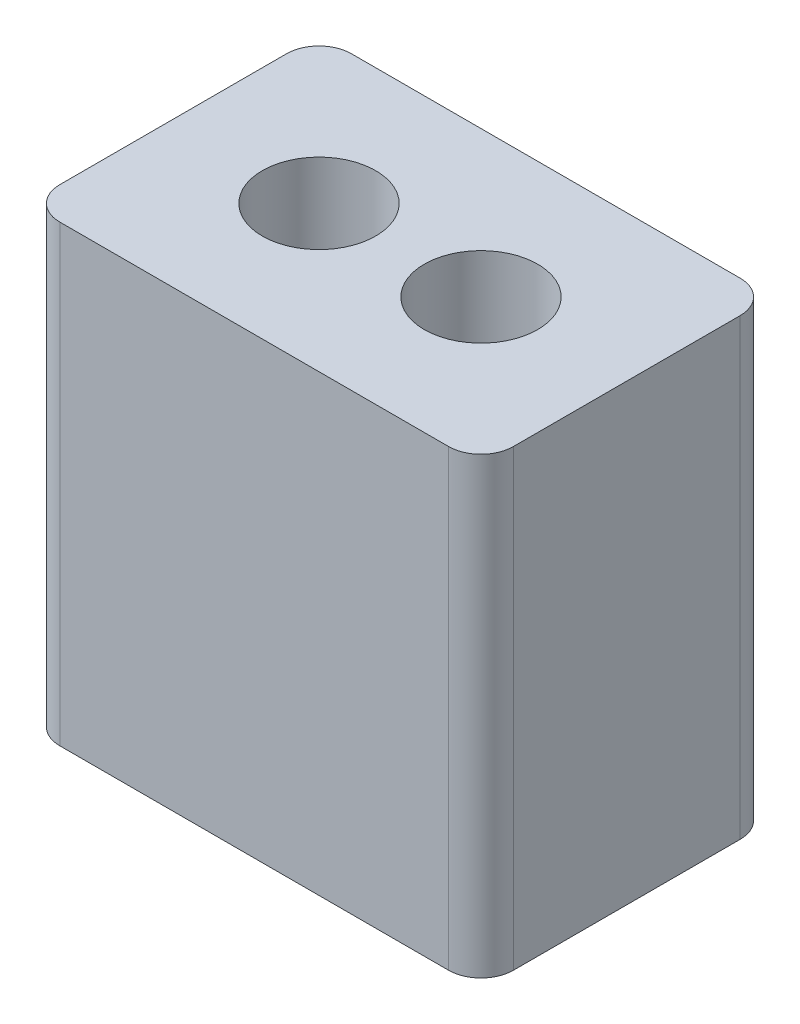
SolidWorks part; units mm, degrees
ref_plane "前视基准面" through (0, 0, 0) normal (0, 0, 1) x (1, 0, 0)
ref_plane "上视基准面" through (0, 0, 0) normal (0, 1, 0) x (1, 0, 0)
ref_plane "右视基准面" through (0, 0, 0) normal (1, 0, 0) x (0, 0, -1)
sketch "草图1" plane through (0, 0, 0) normal (0, 1, 0) x (1, 0, 0)
  line L0 (-7, 4.5) -> (7, -4.5) construction
  line L1 (-7, 4.5) -> (7, 4.5)
  line L2 (-7, 4.5) -> (-7, -4.5)
  line L3 (-7, -4.5) -> (7, -4.5)
  line L4 (7, 4.5) -> (7, -4.5)
  dimension "D1" = 9
  dimension "D2" = 14
extrude "凸台-拉伸1" add sketch "草图1" along normal blind 14
fillet "圆角1" radius 1 4 edges at (-7, 7, -4.5) (7, 7, -4.5) (7, 7, 4.5) (-7, 7, 4.5)
sketch "草图3" plane through (0, 14, 0) normal (0, 1, 0) x (1, 0, 0)
  line L0 (-2.5, 0) -> (2.5, 0) construction
  circle A0 centre (-2.5, 0) radius 1.75
  circle A1 centre (2.5, 0) radius 1.75
  point P2 (0, 0)
  dimension "D2" = 3.5
  dimension "D1" = 5
extrude "切除-拉伸2" cut sketch "草图3" against normal up to next
